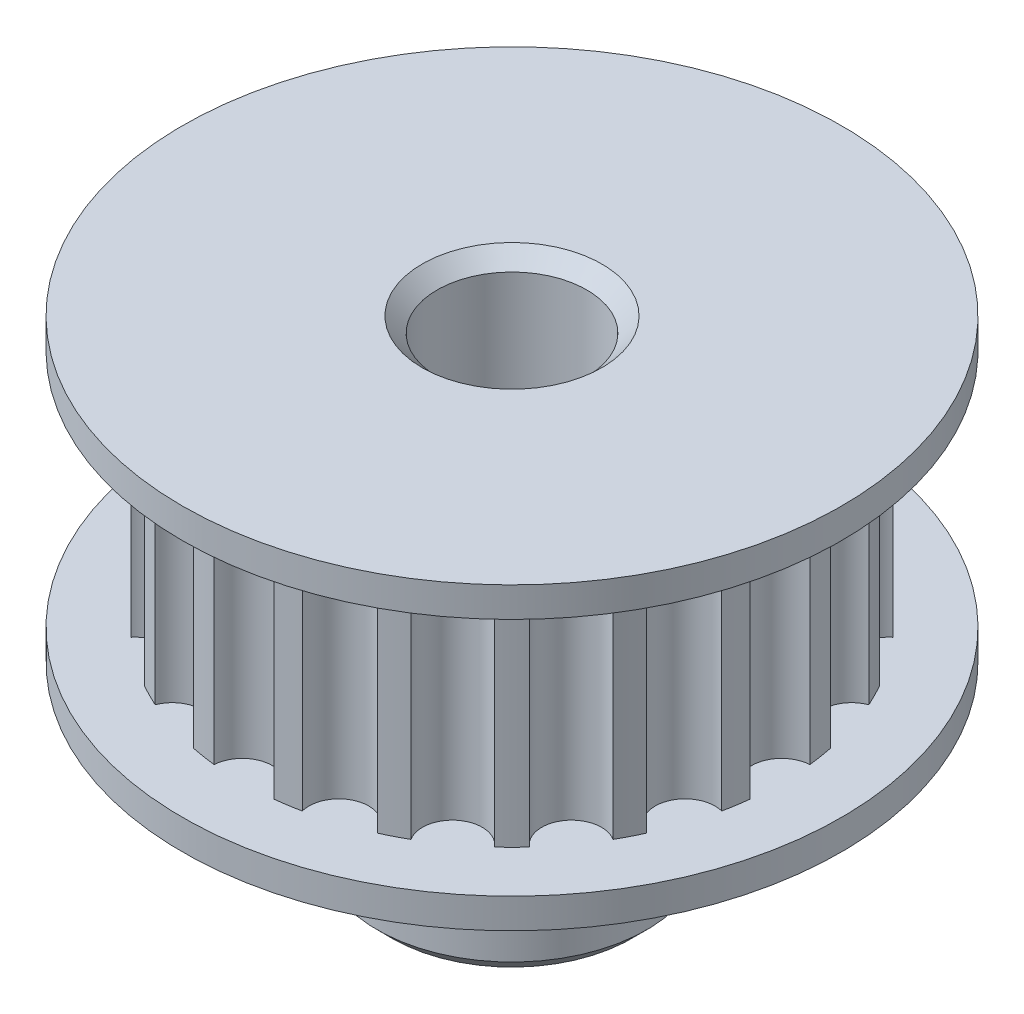
SolidWorks part; units mm, degrees
material "5454-H32"
ref_plane "Alzado" through (0, 0, 0) normal (0, 0, 1) x (1, 0, 0)
ref_plane "Planta" through (0, 0, 0) normal (0, 1, 0) x (1, 0, 0)
ref_plane "Vista lateral" through (0, 0, 0) normal (1, 0, 0) x (0, 0, -1)
sketch "Croquis1" plane through (0, 0, 0) normal (0, 1, 0) x (1, 0, 0)
  circle A0 centre (0, 0) radius 9
  dimension "D1" = 18
extrude "Saliente-Extruir1" add sketch "Croquis1" along normal blind 8
sketch "Croquis3" plane through (0, 8, 0) normal (0, 1, 0) x (1, 0, 0)
  circle A0 centre (0, 0) radius 11
  dimension "D1" = 22
extrude "Saliente-Extruir2" add sketch "Croquis3" along normal blind 1
sketch "Croquis4" plane through (0, 0, 0) normal (0, -1, 0) x (1, 0, 0)
  circle A0 centre (0, 0) radius 11
  circle A1 centre (0, 0) radius 11 construction
extrude "Saliente-Extruir3" add sketch "Croquis4" along normal blind 1
sketch "Croquis5" plane through (0, -1, 0) normal (0, -1, 0) x (1, 0, 0)
  circle A0 centre (0, 0) radius 4.5
  dimension "D1" = 9
extrude "Saliente-Extruir4" add sketch "Croquis5" along normal blind 6
sketch "Croquis6" plane through (0, 9, 0) normal (0, 1, 0) x (1, 0, 0)
  circle A0 centre (0, 0) radius 2.5
  dimension "D1" = 5
extrude "Cortar-Extruir1" cut sketch "Croquis6" against normal through all
sketch "Croquis7" plane through (0, 0, 0) normal (0, 0, 1) x (1, 0, 0)
  line L2 (8.5653, -4) -> (-9.5125, -4) construction
  line L3 (-4.5, -1) -> (4.5, -1) construction
  line L4 (-4.5, -7) -> (4.5, -7) construction
  circle A0 centre (-0.5925, -4) radius 1
  dimension "D1" = 2
extrude "Cortar-Extruir2" cut sketch "Croquis7" against normal through all
sketch "Croquis8" plane through (0, 8, 0) normal (0, -1, 0) x (1, 0, 0)
  line L0 (0, 0) -> (0, -13.2552) construction
  circle A0 centre (0, -9) radius 1
  circle A1 centre (0, 0) radius 9 construction
  dimension "D1" = 2
extrude "Cortar-Extruir5" cut sketch "Croquis8" along normal up to surface (8 mm away) up to face at (0, 0, -11)
pattern_circular "MatrizC1" count 20 over 360 about axis through (0, 0, 0) along (0, 1, 0) of "Cortar-Extruir5"
chamfer "Chaflán1" distance 0.5 angle 45 3 edges at (0, -1, -4.5) (0, -7, -4.5) (0, 9, 2.5)
